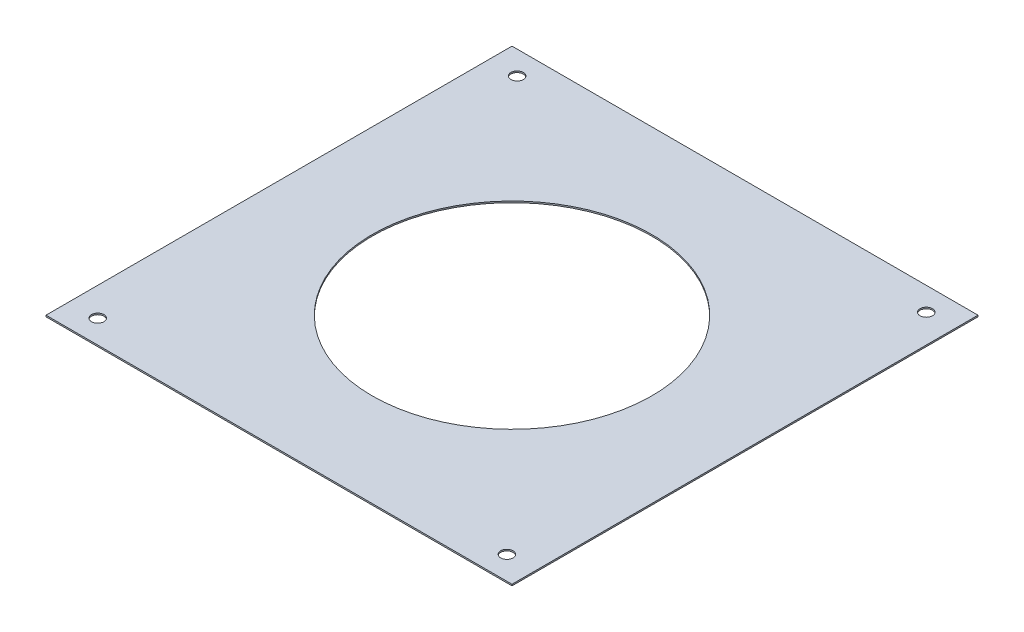
SolidWorks part; units mm, degrees
ref_plane "Front Plane" through (0, 0, 0) normal (0, 0, 1) x (1, 0, 0)
ref_plane "Top Plane" through (0, 0, 0) normal (0, 1, 0) x (1, 0, 0)
ref_plane "Right Plane" through (0, 0, 0) normal (1, 0, 0) x (0, 0, -1)
sketch "Sketch1" plane through (0, 0, 0) normal (0, 1, 0) x (1, 0, 0)
  line L1 (-127, -127) -> (127, -127)
  line L2 (-127, -127) -> (-127, 127)
  line L3 (-127, 127) -> (127, 127)
  line L4 (127, -127) -> (127, 127)
  line L5 (-127, -127) -> (127, 127) construction
  line L6 (-127, 127) -> (127, -127) construction
  line L7 (-111.506, -114.3) -> (111.506, -114.3) construction
  line L8 (-111.506, -114.3) -> (-111.506, 114.3) construction
  line L9 (-111.506, 114.3) -> (111.506, 114.3) construction
  line L10 (111.506, -114.3) -> (111.506, 114.3) construction
  line L11 (-111.506, -114.3) -> (111.506, 114.3) construction
  line L12 (-111.506, 114.3) -> (111.506, -114.3) construction
  circle A0 centre (-111.506, 114.3) radius 3.3782
  circle A1 centre (111.506, 114.3) radius 3.3782
  circle A2 centre (111.506, -114.3) radius 3.3782
  circle A3 centre (-111.506, -114.3) radius 3.3782
  point P0 (0, 0)
  point P6 (0, 0)
  dimension "D4" = 6.7564
  dimension "D1" = 254
  dimension "D2" = 228.6
  dimension "D3" = 223.012
extrude "Boss-Extrude1" add sketch "Sketch1" along normal blind 0.7937
sketch "Sketch2" plane through (0, 0.7937, 0) normal (0, 1, 0) x (1, 0, 0)
  circle A0 centre (0, 0) radius 76.2
  dimension "D1" = 152.4
extrude "Cut-Extrude1" cut sketch "Sketch2" against normal blind 0.7937
